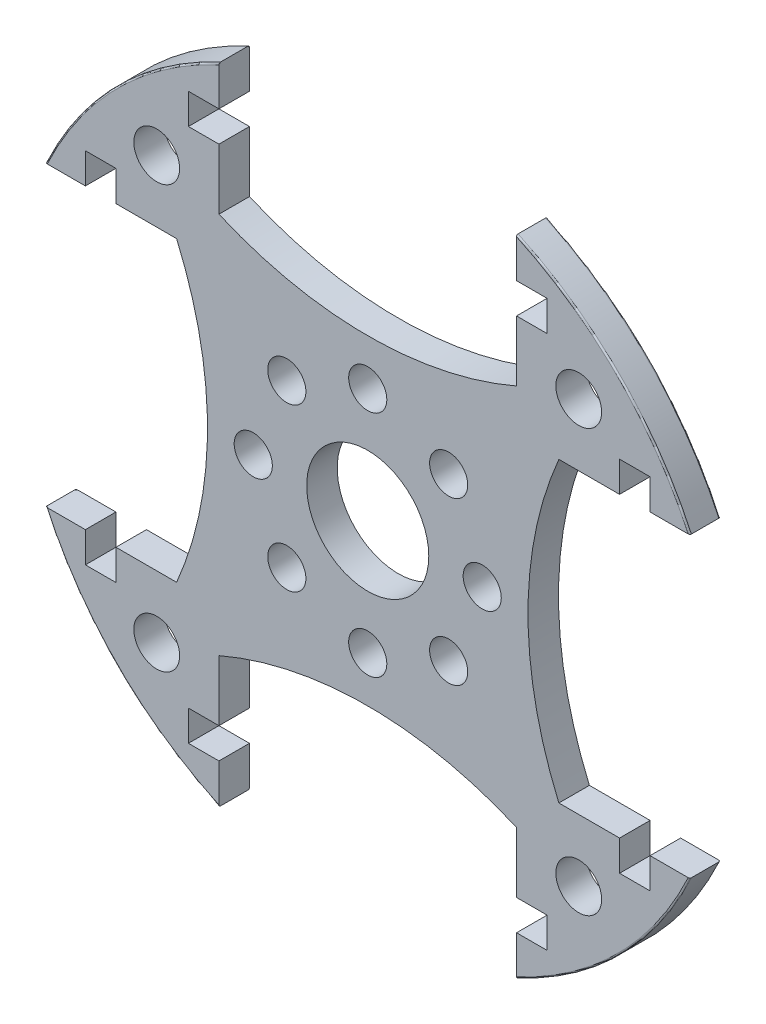
SolidWorks part; units mm, degrees
material "3.1655 (EN AW-2011)"
ref_plane "Спереди" through (0, 0, 0) normal (0, 0, 1) x (1, 0, 0)
ref_plane "Сверху" through (0, 0, 0) normal (0, 1, 0) x (1, 0, 0)
ref_plane "Справа" through (0, 0, 0) normal (1, 0, 0) x (0, 0, -1)
sketch "Эскиз2" plane through (0, 0, 0) normal (0, 0, 1) x (1, 0, 0)
  line L0 (-9.75, 16.5) -> (-9.75, 12.5236)
  line L1 (9.75, 18.5) -> (9.75, 21.1069)
  line L2 (16.4402, 16.4402) -> (13.8257, 13.8257) construction
  line L3 (-18.5, 9.75) -> (-21.1069, 9.75)
  line L4 (21.1069, 9.75) -> (18.5, 9.75)
  line L5 (12.5236, -9.75) -> (16.5, -9.75)
  line L6 (22.1458, 9.75) -> (12.5236, 9.75) construction
  line L7 (22.1458, 9.25) -> (12.8542, 9.25) construction
  line L8 (12.5236, -9.75) -> (22.1458, -9.75) construction
  line L9 (12.8542, -9.25) -> (22.1458, -9.25) construction
  line L10 (9.75, -21.1069) -> (9.75, -18.5)
  line L11 (-9.75, -12.5236) -> (-9.75, -16.5)
  line L12 (-21.1069, -9.75) -> (-18.5, -9.75)
  line L13 (-12.5236, 9.75) -> (-16.5, 9.75)
  line L14 (-9.75, 21.1069) -> (-9.75, 18.5)
  line L15 (9.75, 12.5236) -> (9.75, 16.5)
  line L16 (18.5, 9.75) -> (18.5, 11.75)
  line L17 (17.5, 9.75) -> (17.5, 13.4682) construction
  line L18 (18.5, 9.75) -> (18.5, 13.4682) construction
  line L19 (16.5, 9.75) -> (16.5, 13.4682) construction
  line L20 (18.5, 9.25) -> (18.5, 13.4682) construction
  line L21 (16.5, 9.25) -> (16.5, 13.4682) construction
  line L22 (17.5, 9.25) -> (17.5, 13.4682) construction
  line L23 (18.5, 11.75) -> (16.5, 11.75)
  line L24 (16.5, 11.75) -> (16.5, 9.75)
  line L25 (0, 0) -> (38.1468, 0) construction
  line L26 (16.5, -11.75) -> (16.5, -9.75)
  line L27 (18.5, -11.75) -> (16.5, -11.75)
  line L28 (18.5, -9.75) -> (18.5, -11.75)
  line L29 (11.75, -18.5) -> (11.75, -16.5)
  line L30 (11.75, -16.5) -> (9.75, -16.5)
  line L31 (9.75, -18.5) -> (11.75, -18.5)
  line L32 (-11.75, -16.5) -> (-9.75, -16.5)
  line L33 (-11.75, -18.5) -> (-11.75, -16.5)
  line L34 (-9.75, -18.5) -> (-11.75, -18.5)
  line L35 (-18.5, -11.75) -> (-16.5, -11.75)
  line L36 (-16.5, -11.75) -> (-16.5, -9.75)
  line L37 (-18.5, -9.75) -> (-18.5, -11.75)
  line L38 (-16.5, 11.75) -> (-16.5, 9.75)
  line L39 (-18.5, 11.75) -> (-16.5, 11.75)
  line L40 (-18.5, 9.75) -> (-18.5, 11.75)
  line L41 (-11.75, 18.5) -> (-11.75, 16.5)
  line L42 (-11.75, 16.5) -> (-9.75, 16.5)
  line L43 (-9.75, 18.5) -> (-11.75, 18.5)
  line L44 (11.75, 16.5) -> (9.75, 16.5)
  line L45 (11.75, 18.5) -> (11.75, 16.5)
  line L46 (9.75, 18.5) -> (11.75, 18.5)
  line L47 (-16.5, -9.75) -> (-12.5236, -9.75)
  line L48 (18.5, -9.75) -> (21.1069, -9.75)
  line L49 (16.5, 9.75) -> (12.5236, 9.75)
  line L50 (9.75, -16.5) -> (9.75, -12.5236)
  line L51 (-9.75, -18.5) -> (-9.75, -21.1069)
  arc A0 (21.1069, 9.75) -> (9.75, 21.1069) centre (0, 0) ccw
  circle A1 centre (0, 0) radius 4
  circle A3 centre (0, 0) radius 7.5 construction
  circle A4 centre (0, 7.5) radius 1.25
  circle A5 centre (5.3033, 5.3033) radius 1.25
  circle A6 centre (7.5, 0) radius 1.25
  circle A7 centre (5.3033, -5.3033) radius 1.25
  circle A8 centre (0, -7.5) radius 1.25
  circle A9 centre (-5.3033, -5.3033) radius 1.25
  circle A10 centre (-7.5, 0) radius 1.25
  circle A11 centre (-5.3033, 5.3033) radius 1.25
  arc A13 (12.8542, 9.25) -> (12.8542, -9.25) centre (35, 0) ccw construction
  arc A14 (12.5236, 9.75) -> (12.5236, -9.75) centre (35, 0) ccw
  arc A15 (9.75, -12.5236) -> (-9.75, -12.5236) centre (0, -35) ccw
  arc A16 (-12.5236, -9.75) -> (-12.5236, 9.75) centre (-35, 0) ccw
  arc A17 (-9.75, 12.5236) -> (9.75, 12.5236) centre (0, 35) ccw
  arc A18 (-9.75, 21.1069) -> (-21.1069, 9.75) centre (0, 0) ccw
  arc A19 (-21.1069, -9.75) -> (-9.75, -21.1069) centre (0, 0) ccw
  arc A20 (9.75, -21.1069) -> (21.1069, -9.75) centre (0, 0) ccw
  circle A22 centre (13.8257, 13.8257) radius 1.5
  circle A23 centre (13.8257, -13.8257) radius 1.5
  circle A24 centre (-13.8257, -13.8257) radius 1.5
  circle A25 centre (-13.8257, 13.8257) radius 1.5
  point P24 (0, 0)
  point P54 (0, 0)
  point P63 (0, 0)
  point P104 (0, 0)
  dimension "D1" = 46.5
  dimension "D2" = 15
  dimension "D3" = 8
  dimension "D4" = 2.5
  dimension "D6" = 3
  dimension "D9" = 2
  dimension "D5" = 0.5
  dimension "D7" = 1
  dimension "D8" = 1
extrude "Бобышка-Вытянуть1" add sketch "Эскиз2" along normal blind 2
fillet "Скругление1" radius 0.1 8 edges at (16.4402, -16.4402, 0) (-16.4402, -16.4402, 0) (-16.4402, 16.4402, 0) (16.4402, 16.4402, 0) (16.4402, -16.4402, 2) (-16.4402, -16.4402, 2) (16.4402, 16.4402, 2) (-16.4402, 16.4402, 2)
